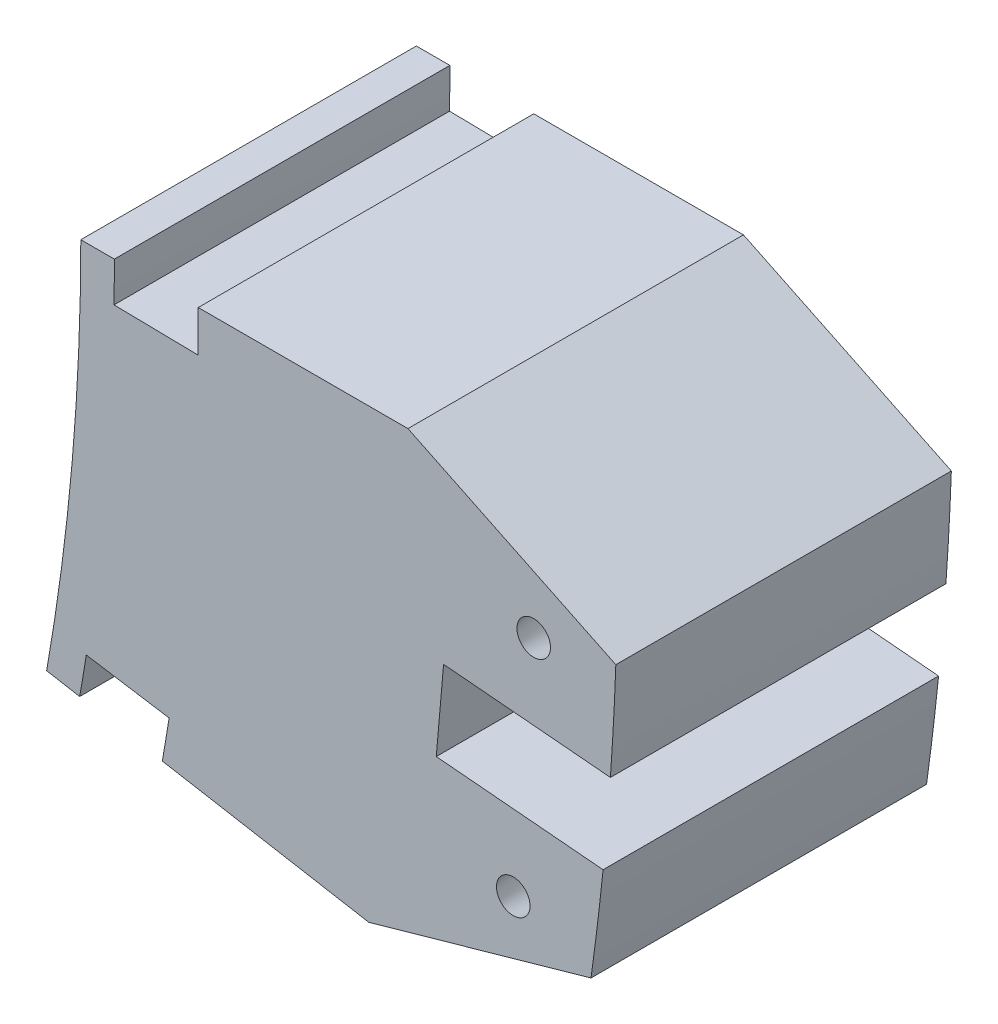
SolidWorks part; units mm, degrees
ref_plane "前视基准面" through (0, 0, 0) normal (0, 0, 1) x (1, 0, 0)
ref_plane "上视基准面" through (0, 0, 0) normal (0, 1, 0) x (1, 0, 0)
ref_plane "右视基准面" through (0, 0, 0) normal (1, 0, 0) x (0, 0, -1)
sketch "草图1" plane through (0, 0, 0) normal (0, 0, 1) x (1, 0, 0)
  line L0 (670, 0) -> (830, 0)
  line L1 (659.8212, -116.3443) -> (817.3904, -144.128)
  arc A0 (659.8212, -116.3443) -> (670, 0) centre (0, 0) ccw
  arc A1 (817.3904, -144.128) -> (830, 0) centre (0, 0) ccw
  dimension "D1" = 10
  dimension "D2" = 830
  dimension "D3" = 670
extrude "凸台-拉伸1" add sketch "草图1" along normal blind 100
sketch "草图2" plane through (0, 0, 100) normal (0, 0, 1) x (1, 0, 0)
  line L0 (0, 0) -> (826.8416, -72.3393) construction
  arc A0 (817.3904, -144.128) -> (830, 0) centre (0, 0) ccw construction
ref_plane "基准面1" through (0, 0, 0) normal (-0.0872, -0.9962, 0) x (0.9962, -0.0872, 0)
sketch "草图3" plane through (0, 0, 100) normal (0, 0, 1) x (1, 0, 0)
  line L0 (826.8416, -72.3393) -> (0, 0) construction
  line L1 (826.8416, -72.3393) -> (777.0319, -67.9815) construction
  line L2 (777.0319, -67.9815) -> (778.1213, -55.529)
  line L3 (778.1213, -55.529) -> (827.8373, -59.8786)
  line L4 (777.0319, -67.9815) -> (775.9424, -80.4339)
  line L5 (775.9424, -80.4339) -> (825.6584, -84.7835)
  arc A0 (817.3904, -144.128) -> (830, 0) centre (0, 0) ccw construction
  arc A2 (825.6584, -84.7835) -> (827.8373, -59.8786) centre (0, 0) ccw
  arc A3 (825.6584, -84.7835) -> (827.8373, -59.8786) centre (0, 0) ccw
  arc A4 (825.6584, -84.7835) -> (829.2756, -34.6705) centre (0, 0) ccw
  arc M6 (817.3904, -144.128) -> (830, 0) centre (0, 0) ccw
  dimension "D1" = 12.5
  dimension "D2" = 12.5
  dimension "D3" = 50
extrude "切除-拉伸1" cut sketch "草图3" against normal through all contours L4 L5 L3 L2 M6
sketch "草图4" plane through (0, 0, 100) normal (0, 0, 1) x (1, 0, 0)
  line L0 (776.1603, -77.9434) -> (825.97, -82.3012)
  line L1 (825.97, -82.3012) -> (821.6123, -132.1109)
  line L2 (821.6123, -132.1109) -> (771.8025, -127.7532)
  line L3 (771.8025, -127.7532) -> (776.1603, -77.9434)
  line L5 (0, 0) -> (826.8416, -72.3393) construction
  line L6 (771.8025, -127.7532) -> (825.97, -82.3012) construction
  line L7 (776.1603, -77.9434) -> (821.6123, -132.1109) construction
  point P6 (798.8863, -105.0272)
  dimension "D1" = 10
  dimension "D2" = 780
  dimension "D3" = 50
ref_plane "基准面2" through (-3.0505, -34.8668, 0) normal (-0.0872, -0.9962, 0) x (-0.9962, 0.0872, 0)
sketch "草图5" plane through (-3.0505, -34.8668, 0) normal (-0.0872, -0.9962, 0) x (-0.9962, 0.0872, 0)
  line L0 (-805, -100) -> (-810, -100)
  line L1 (-810, -100) -> (-818.6824, -50.7596)
  line L2 (-818.6824, -50.7596) -> (-818.6824, 0)
  line L3 (-818.6824, 0) -> (-805, 0)
  line L4 (-805, 0) -> (-805, -100)
  dimension "D1" = 5
  dimension "D2" = 50
  dimension "D3" = 100
  dimension "D4" = 100
revolve "切除-旋转1" cut sketch "草图5" angle 360 about L4
mirror "镜向1" about plane through (0, 0, 0) normal (-0.0872, -0.9962, 0) of "切除-旋转1"
sketch "草图6" plane through (0, 0, 0) normal (0, 0, -1) x (-1, 0, 0)
  line L1 (-669.6693, -118.0808) -> (-694.2895, -122.422)
  line L2 (-659.8212, -116.3443) -> (-817.3904, -144.128) construction
  line L4 (-671.6281, -106.3754) -> (-696.3203, -110.2863)
  line L5 (-671.6281, -106.3754) -> (0, 0) construction
  line L6 (-777.0319, -67.9815) -> (-667.4504, -58.3943) construction
  line L7 (-778.1213, -55.529) -> (-775.9424, -80.4339) construction
  line L8 (-679.8964, -11.8676) -> (0, 0) construction
  line L9 (-679.8964, -11.8676) -> (-704.8926, -12.3039)
  line L10 (-680, 0) -> (-705, 0)
  line L11 (-669.6693, -118.0808) -> (0, 0) construction
  arc A2 (-671.6281, -106.3754) -> (-669.6693, -118.0808) centre (0, 0) ccw
  arc A3 (-696.3203, -110.2863) -> (-694.2895, -122.422) centre (0, 0) ccw
  arc A5 (-670, 0) -> (-659.8212, -116.3443) centre (0, 0) ccw construction
  arc A6 (-704.8926, -12.3039) -> (-705, 0) centre (0, 0) cw
  arc A7 (-679.8964, -11.8676) -> (-680, 0) centre (0, 0) cw
  line M13 (-817.3904, -144.128) -> (-659.8212, -116.3443)
  arc M14 (-659.8212, -116.3443) -> (-670, 0) centre (0, 0) cw
  line M15 (-670, 0) -> (-830, 0)
  dimension "D1" = 25
  dimension "D2" = 705
  dimension "D4" = 1
extrude "切除-拉伸2" cut sketch "草图6" against normal through all contours L4 A3 M13 M14 | A6 L9 M14 M15
sketch "草图7" plane through (0, 0, 100) normal (0, 0, 1) x (1, 0, 0)
  line L0 (829.4591, -29.9588) -> (767.5, 0)
  line L1 (830, 0) -> (705, 0) construction
  line L2 (767.5, 0) -> (830, 0)
  line L3 (-118.3034, 10.3502) -> (118.3034, -10.3502) construction
  line L4 (755.84, -133.275) -> (817.3904, -144.128)
  line L5 (822.0601, -114.5304) -> (755.84, -133.275)
  arc A0 (827.8373, -59.8786) -> (830, 0) centre (0, 0) ccw construction
  arc A1 (830, 0) -> (829.4591, -29.9588) centre (0, 0) cw
  arc A2 (817.3904, -144.128) -> (822.0601, -114.5304) centre (0, 0) ccw
  line M7 (694.2895, -122.422) -> (817.3904, -144.128)
  arc M8 (817.3904, -144.128) -> (825.6584, -84.7835) centre (0, 0) ccw
  arc M12 (827.8373, -59.8786) -> (830, 0) centre (0, 0) ccw
  line M13 (830, 0) -> (705, 0)
extrude "切除-拉伸3" cut sketch "草图7" against normal up to next contours L0 M12 M13 | L5 M8 M7
